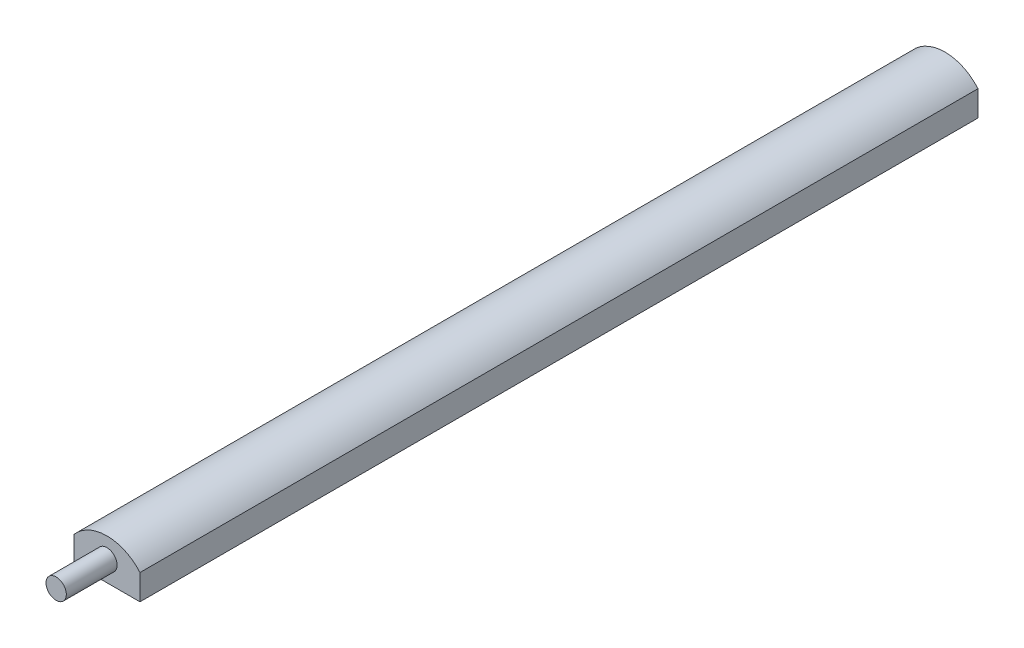
SolidWorks part; units mm, degrees
ref_plane "Front Plane" through (0, 0, 0) normal (0, 0, 1) x (1, 0, 0)
ref_plane "Top Plane" through (0, 0, 0) normal (0, 1, 0) x (1, 0, 0)
ref_plane "Right Plane" through (0, 0, 0) normal (1, 0, 0) x (0, 0, -1)
sketch "Sketch1" plane through (0, 0, 0) normal (0, 0, 1) x (1, 0, 0)
  line L0 (6.5, 0) -> (6.5, 8) construction
  line L1 (0, 0) -> (13, 0)
  line L2 (0, 0) -> (0, 5)
  line L3 (0, 5) -> (13, 5) construction
  line L4 (13, 0) -> (13, 5)
  arc A0 (0, 5) -> (13, 5) centre (6.5, -0.5417) cw
  dimension "D1" = 13
  dimension "D2" = 5
  dimension "D3" = 8
extrude "Boss-Extrude1" add sketch "Sketch1" along normal blind 165
sketch "Sketch2" plane through (0, 0, 165) normal (0, 0, 1) x (1, 0, 0)
  line L0 (0, 0) -> (13, 0) construction
  line L1 (6.5, 0) -> (6.5, 8) construction
  circle A0 centre (6.5, 4) radius 2
  arc A1 (13, 5) -> (0, 5) centre (6.5, -0.5417) ccw construction
  point P4 (6.5, 0)
  point P11 (6.5, 4)
  dimension "D1" = 4
extrude "Boss-Extrude2" add sketch "Sketch2" along normal blind 10
